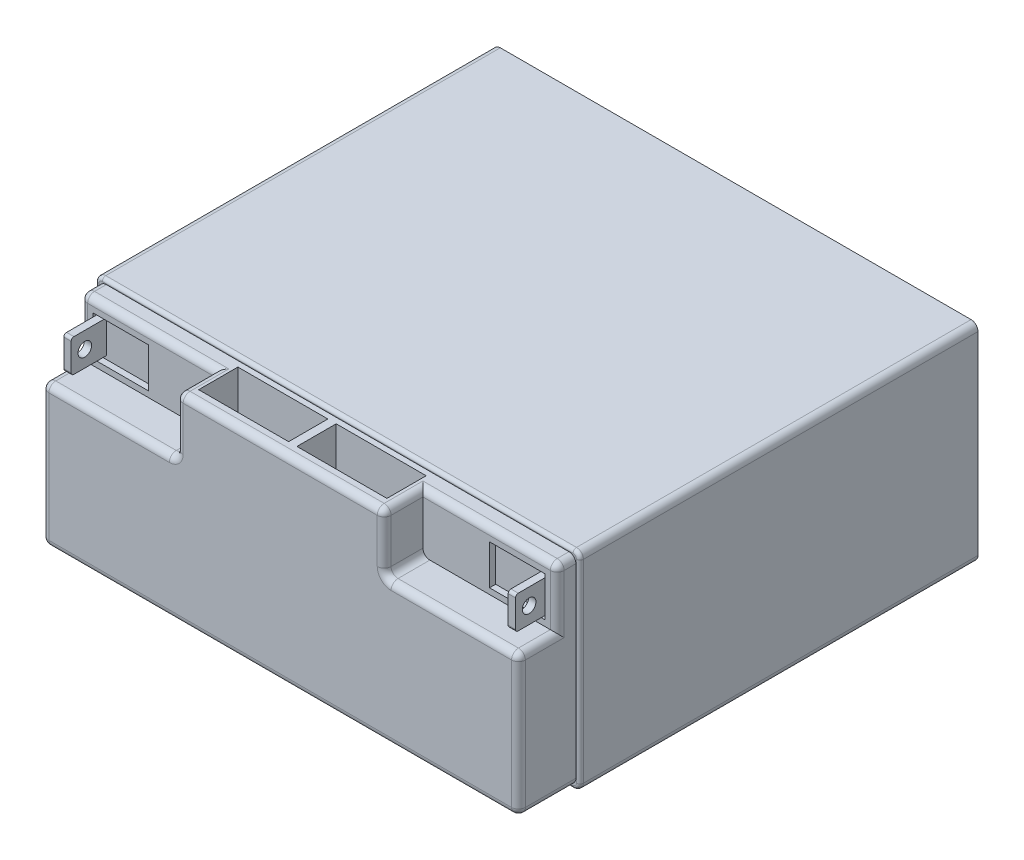
SolidWorks part; units mm, degrees
ref_plane "Front Plane" through (0, 0, 0) normal (0, 0, 1) x (1, 0, 0)
ref_plane "Top Plane" through (0, 0, 0) normal (0, 1, 0) x (1, 0, 0)
ref_plane "Right Plane" through (0, 0, 0) normal (1, 0, 0) x (0, 0, -1)
ref_plane "Plane1" through (0, -62.2132, 0) normal (0, -1, 0) x (1, 0, 0)
sketch "Sketch1" plane through (0, -62.2132, 0) normal (0, -1, 0) x (1, 0, 0)
  line L0 (-33.1131, 0) -> (144.6869, 0)
  line L1 (144.6869, 0) -> (144.6869, 146.05)
  line L2 (144.6869, 146.05) -> (-33.1131, 146.05)
  line L3 (-33.1131, 146.05) -> (-33.1131, 0)
extrude "Boss-Extrude1" add sketch "Sketch1" against normal blind 76.2
sketch "Sketch2" plane through (0, 0, 146.05) normal (0, 0, 1) x (1, 0, 0)
  line L0 (143.2096, -60.7358) -> (-31.6357, -60.7358)
  line L1 (-31.6357, -60.7358) -> (-31.6357, 12.5094)
  line L2 (-31.6357, 12.5094) -> (143.2096, 12.5094)
  line L3 (143.2096, 12.5094) -> (143.2096, -60.7358)
extrude "Boss-Extrude2" add sketch "Sketch2" along normal blind 21.082
sketch "Sketch3" plane through (-31.6357, 0, 0) normal (-1, 0, 0) x (0, 0, 1)
  line L0 (152.908, 12.5094) -> (152.908, -8.8266)
  line L1 (152.908, -8.8266) -> (167.132, -8.8266)
  line L2 (167.132, -8.8266) -> (167.132, 12.5094)
  line L3 (167.132, 12.5094) -> (152.908, 12.5094)
extrude "Cut-Extrude1" cut sketch "Sketch3" against normal blind 49.276
sketch "Sketch4" plane through (0, 0, 152.908) normal (0, 0, 1) x (1, 0, 0)
  line L0 (-24.3791, -5.3674) -> (-27.0726, -5.3674)
  line L1 (-27.0726, -5.3674) -> (-27.0726, 6.6326)
  line L2 (-27.0726, 6.6326) -> (-24.3791, 6.6326)
  line L3 (-24.3791, 6.6326) -> (-24.3791, -5.3674)
extrude "Boss-Extrude3" add sketch "Sketch4" along normal blind 10.746
sketch "Sketch5" plane through (0, 0, 152.908) normal (0, 0, 1) x (1, 0, 0)
  line L0 (-27.0726, 6.6326) -> (-24.3791, 6.6326)
  line L1 (-24.3791, 6.6326) -> (-24.3791, -5.3674)
  line L2 (-24.3791, -5.3674) -> (-27.0726, -5.3674)
  line L3 (-27.0726, -5.3674) -> (-27.0726, -6.6776)
  line L4 (-27.0726, -6.6776) -> (-6.7872, -6.6776)
  line L5 (-6.7872, -6.6776) -> (-6.7872, 7.9428)
  line L6 (-6.7872, 7.9428) -> (-27.0726, 7.9428)
  line L7 (-27.0726, 7.9428) -> (-27.0726, 6.6326)
extrude "Cut-Extrude2" cut sketch "Sketch5" against normal blind 2.254
sketch "Sketch6" plane through (0, 12.5094, 0) normal (0, 1, 0) x (-1, 0, 0)
  line L0 (-143.2096, 152.908) -> (-93.9336, 152.908)
  line L1 (-93.9336, 152.908) -> (-93.9336, 167.132)
  line L2 (-93.9336, 167.132) -> (-143.2096, 167.132)
  line L3 (-143.2096, 167.132) -> (-143.2096, 152.908)
extrude "Cut-Extrude3" cut sketch "Sketch6" against normal blind 21.336
sketch "Sketch7" plane through (0, 0, 152.908) normal (0, 0, 1) x (1, 0, 0)
  line L0 (138.6465, -5.3674) -> (135.9529, -5.3674)
  line L1 (135.9529, -5.3674) -> (135.9529, 6.6326)
  line L2 (135.9529, 6.6326) -> (138.6465, 6.6326)
  line L3 (138.6465, 6.6326) -> (138.6465, -5.3674)
extrude "Boss-Extrude4" add sketch "Sketch7" along normal blind 10.746
sketch "Sketch8" plane through (0, 0, 152.908) normal (0, 0, 1) x (1, 0, 0)
  line L0 (138.6465, -5.3674) -> (135.9529, -5.3674)
  line L1 (135.9529, -5.3674) -> (135.9529, 6.6326)
  line L2 (135.9529, 6.6326) -> (138.6465, 6.6326)
  line L3 (138.6465, 6.6326) -> (138.6465, 7.9428)
  line L4 (138.6465, 7.9428) -> (118.361, 7.9428)
  line L5 (118.361, 7.9428) -> (118.361, -6.6776)
  line L6 (118.361, -6.6776) -> (138.6465, -6.6776)
  line L7 (138.6465, -6.6776) -> (138.6465, -5.3674)
extrude "Cut-Extrude4" cut sketch "Sketch8" against normal blind 2.254
sketch "Sketch9" plane through (0, 12.5094, 0) normal (0, 1, 0) x (-1, 0, 0)
  line L0 (-90.3309, 148.1138) -> (-57.3109, 148.1138)
  line L1 (-57.3109, 148.1138) -> (-57.3109, 162.5135)
  line L2 (-57.3109, 162.5135) -> (-90.3309, 162.5135)
  line L3 (-90.3309, 162.5135) -> (-90.3309, 148.1138)
extrude "Cut-Extrude5" cut sketch "Sketch9" against normal blind 19.05
sketch "Sketch10" plane through (0, 12.5094, 0) normal (0, 1, 0) x (-1, 0, 0)
  line L0 (-54.2629, 148.1138) -> (-21.2429, 148.1138)
  line L1 (-21.2429, 148.1138) -> (-21.2429, 162.5135)
  line L2 (-21.2429, 162.5135) -> (-54.2629, 162.5135)
  line L3 (-54.2629, 162.5135) -> (-54.2629, 148.1138)
extrude "Cut-Extrude6" cut sketch "Sketch10" against normal blind 19.05
sketch "Sketch11" plane through (0, -60.7358, 0) normal (0, -1, 0) x (1, 0, 0)
  line L0 (56.8496, 162.8434) -> (56.8496, 147.6421)
  line L1 (56.8496, 147.6421) -> (120.3496, 147.6421)
  line L2 (120.3496, 147.6421) -> (120.3496, 162.8434)
  line L3 (120.3496, 162.8434) -> (56.8496, 162.8434)
extrude "Cut-Extrude7" cut sketch "Sketch11" against normal blind 19.558
sketch "Sketch12" plane through (0, -60.7358, 0) normal (0, -1, 0) x (1, 0, 0)
  line L0 (-8.7757, 162.8434) -> (-8.7757, 147.6421)
  line L1 (-8.7757, 147.6421) -> (54.7243, 147.6421)
  line L2 (54.7243, 147.6421) -> (54.7243, 162.8434)
  line L3 (54.7243, 162.8434) -> (-8.7757, 162.8434)
extrude "Cut-Extrude8" cut sketch "Sketch12" against normal blind 19.558
hole_wizard "Ø5.0 (5) Diameter Hole1" positions "Sketch14" profile "Sketch13" hole size "Ø5.0" standard "ANSI Metric"
sketch "Sketch14" plane through (135.9529, 0, 0) normal (-1, 0, 0) x (0, 0, 1)
  point P0 (158.654, 0.6326)
sketch "Sketch13" plane through (135.9529, 0.6326, 158.654) normal (0, 1, 0) x (0, 0, 1)
  line L0 (0, 0) -> (0, 8.734)
  line L1 (0, 8.734) -> (2.5, 8.734)
  line L2 (2.5, 8.734) -> (2.5, 0)
  line L5 (2.5, 0) -> (0, 0)
  line L11 (0, -6.35) -> (0, 107.95) construction
  dimension "Thru Hole Dia." = 5
  dimension "Thru Hole Depth" = 8.734
hole_wizard "Ø5.0 (5) Diameter Hole2" positions "Sketch16" profile "Sketch15" hole size "Ø5.0" standard "ANSI Metric"
sketch "Sketch16" plane through (-24.3791, 0, 0) normal (1, 0, 0) x (0, 0, -1)
  point P0 (-158.654, 0.6326)
sketch "Sketch15" plane through (-24.3791, 0.6326, 158.654) normal (0, 1, 0) x (0, 0, -1)
  line L0 (0, 0) -> (0, 8.734)
  line L1 (0, 8.734) -> (2.5, 8.734)
  line L2 (2.5, 8.734) -> (2.5, 0)
  line L5 (2.5, 0) -> (0, 0)
  line L11 (0, -6.35) -> (0, 107.95) construction
  dimension "Thru Hole Dia." = 5
  dimension "Thru Hole Depth" = 8.734
fillet "Fillet1" radius 2.54 26 edges at (143.2096, -60.7358, 156.591) (143.2096, 1.8414, 152.908) (143.2096, 12.5094, 149.479) (-31.6357, -60.7358, 156.591) (55.7869, -60.7358, 167.132) (143.2096, -34.7812, 167.132) (143.2096, -8.8266, 160.02) (118.5716, 12.5094, 152.908) (-31.6357, 12.5094, 149.479) (-31.6357, 1.8414, 152.908) (-31.6357, -8.8266, 160.02) (-31.6357, -34.7812, 167.132) (93.9336, 1.8414, 167.132) (118.5716, -8.8266, 167.132) (93.9336, 12.5094, 160.02) (-6.9977, 12.5094, 152.908) (-6.9977, -8.8266, 167.132) (17.6403, 1.8414, 167.132) (55.7869, 12.5094, 167.132) (17.6403, 12.5094, 160.02) (17.6403, -8.8266, 160.02) (-33.1131, 13.9868, 73.025) (93.9336, -8.8266, 160.02) (144.6869, -62.2132, 73.025) (-33.1131, -62.2132, 73.025) (144.6869, 13.9868, 73.025)
fillet "Fillet2" radius 1 4 edges at (-25.7258, -5.3674, 163.654) (-25.7258, 6.6326, 163.654) (137.2997, 6.6326, 163.654) (137.2997, -5.3674, 163.654)
fillet "Fillet3" radius 1.27 8 edges at (-33.1131, -24.1132, 146.05) (-32.3691, 13.2428, 146.05) (-32.3691, -61.4693, 146.05) (55.7869, 13.9868, 146.05) (55.7869, -62.2132, 146.05) (143.943, 13.2428, 146.05) (143.943, -61.4693, 146.05) (144.6869, -24.1132, 146.05)
